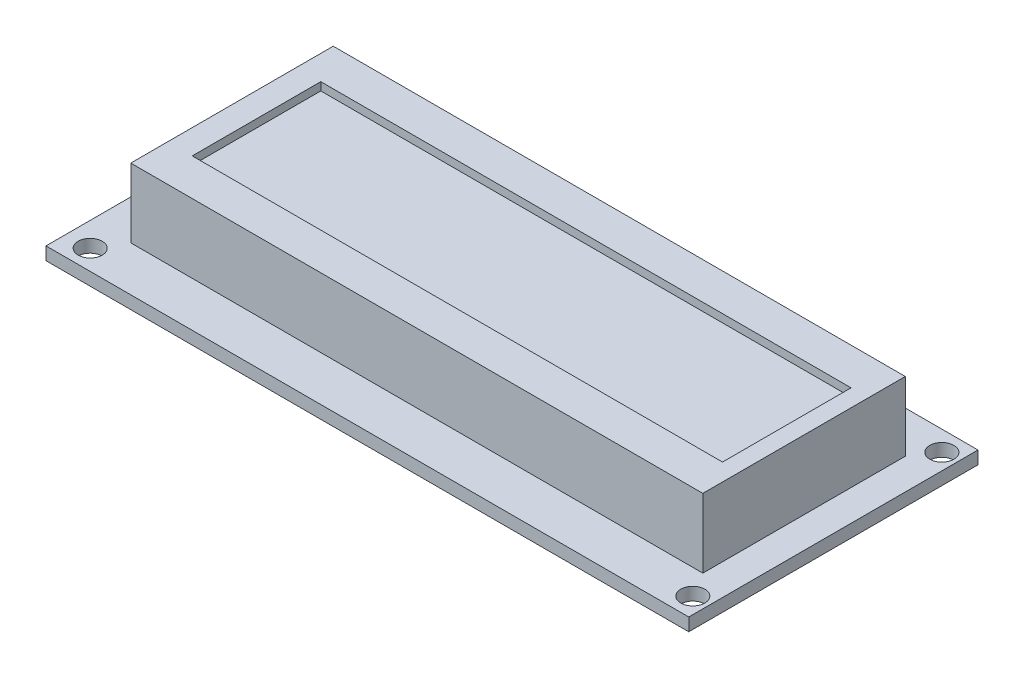
SolidWorks part; units mm, degrees
ref_plane "Front Plane" through (0, 0, 0) normal (0, 0, 1) x (1, 0, 0)
ref_plane "Top Plane" through (0, 0, 0) normal (0, 1, 0) x (1, 0, 0)
ref_plane "Right Plane" through (0, 0, 0) normal (1, 0, 0) x (0, 0, -1)
sketch "Sketch1" plane through (0, 0, 0) normal (0, 1, 0) x (1, 0, 0)
  line L1 (-36.7123, 28.2192) -> (43.2877, 28.2192)
  line L2 (-36.7123, 28.2192) -> (-36.7123, -7.7808)
  line L3 (-36.7123, -7.7808) -> (43.2877, -7.7808)
  line L4 (43.2877, 28.2192) -> (43.2877, -7.7808)
  dimension "D1" = 80
  dimension "D2" = 36
extrude "Boss-Extrude1" add sketch "Sketch1" along normal blind 1.6
sketch "Sketch2" plane through (0, 1.6, 0) normal (0, 1, 0) x (1, 0, 0)
  line L0 (-36.7123, 28.2192) -> (-36.7123, -7.7808) construction
  line L1 (-31.7623, 23.0192) -> (39.4377, 23.0192)
  line L2 (-31.7623, 23.0192) -> (-31.7623, -2.1808)
  line L3 (-31.7623, -2.1808) -> (39.4377, -2.1808)
  line L4 (39.4377, 23.0192) -> (39.4377, -2.1808)
  line L5 (43.2877, 28.2192) -> (-36.7123, 28.2192) construction
  dimension "D1" = 25.2
  dimension "D2" = 71.2
  dimension "D3" = 4.95
  dimension "D4" = 5.2
extrude "Boss-Extrude2" add sketch "Sketch2" along normal blind 8.6
sketch "Sketch3" plane through (0, 1.6, 0) normal (0, 1, 0) x (1, 0, 0)
  line L0 (-36.7123, 28.2192) -> (-36.7123, -7.7808) construction
  line L1 (43.2877, 28.2192) -> (-36.7123, 28.2192) construction
  circle A0 centre (-33.7123, 25.7192) radius 1.5
  circle A1 centre (41.2877, 25.7192) radius 1.5
  circle A2 centre (-33.7123, -5.2808) radius 1.5
  circle A3 centre (41.2877, -5.2808) radius 1.5
  dimension "D1" = 3
  dimension "D3" = 2.5
  dimension "D4" = 75
  dimension "D5" = 31
  dimension "D2" = 2.5
extrude "Cut-Extrude3" cut sketch "Sketch3" against normal blind 13.2
sketch "Sketch4" plane through (0, 1.6, 0) normal (0, 1, 0) x (1, 0, 0)
  line L1 (-28.7123, 18.4192) -> (37.2877, 18.4192)
  line L2 (-28.7123, 18.4192) -> (-28.7123, 2.4192)
  line L3 (-28.7123, 2.4192) -> (37.2877, 2.4192)
  line L4 (37.2877, 18.4192) -> (37.2877, 2.4192)
  line L5 (-36.7123, 28.2192) -> (-36.7123, -7.7808) construction
  line L6 (43.2877, 28.2192) -> (-36.7123, 28.2192) construction
  dimension "D1" = 16
  dimension "D2" = 66
  dimension "D3" = 8
  dimension "D4" = 9.8
sketch "Sketch6" plane through (0, 10.2, 0) normal (0, 1, 0) x (1, 0, 0)
  line L1 (-28.7123, 18.4192) -> (37.2877, 18.4192)
  line L2 (-28.7123, 18.4192) -> (-28.7123, 2.4192)
  line L3 (-28.7123, 2.4192) -> (37.2877, 2.4192)
  line L4 (37.2877, 18.4192) -> (37.2877, 2.4192)
extrude "Cut-Extrude4" cut sketch "Sketch6" against normal blind 1
sketch "Sketch7" plane through (0, 1.6, 0) normal (0, 1, 0) x (1, 0, 0)
  line L0 (-36.7123, 28.2192) -> (-36.7123, -7.7808) construction
  line L1 (43.2877, 28.2192) -> (-36.7123, 28.2192) construction
  circle A0 centre (-28.7123, 25.7192) radius 0.5
  circle A1 centre (-26.1723, 25.7192) radius 0.5
  circle A2 centre (-23.6323, 25.7192) radius 0.5
  circle A3 centre (-21.0923, 25.7192) radius 0.5
  circle A4 centre (-18.5523, 25.7192) radius 0.5
  circle A5 centre (-16.0123, 25.7192) radius 0.5
  circle A6 centre (-13.4723, 25.7192) radius 0.5
  circle A7 centre (-10.9323, 25.7192) radius 0.5
  circle A8 centre (-8.3923, 25.7192) radius 0.5
  circle A9 centre (-5.8523, 25.7192) radius 0.5
  circle A10 centre (-3.3123, 25.7192) radius 0.5
  circle A11 centre (-0.7723, 25.7192) radius 0.5
  circle A12 centre (1.7677, 25.7192) radius 0.5
  circle A13 centre (4.3077, 25.7192) radius 0.5
  circle A14 centre (6.8477, 25.7192) radius 0.5
  circle A15 centre (9.3877, 25.7192) radius 0.5
  dimension "D1" = 8
  dimension "D3" = 2.5
  dimension "D2" = 16
extrude "Cut-Extrude5" cut sketch "Sketch7" against normal blind 21
